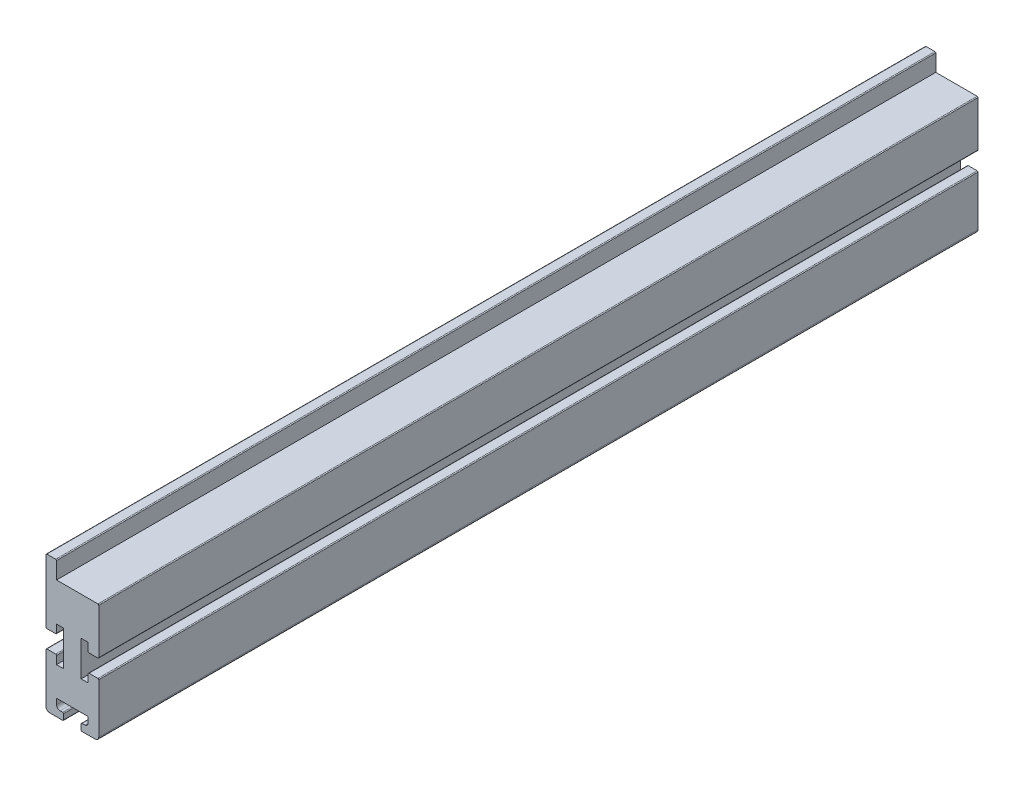
SolidWorks part; units mm, degrees
ref_plane "Alzado" through (0, 0, 0) normal (0, 0, 1) x (1, 0, 0)
ref_plane "Planta" through (0, 0, 0) normal (0, 1, 0) x (1, 0, 0)
ref_plane "Vista lateral" through (0, 0, 0) normal (1, 0, 0) x (0, 0, -1)
sketch "Croquis1" plane through (0, 0, 0) normal (0, 0, 1) x (1, 0, 0)
  line L1 (-4.4519, 8.3151) -> (1.5481, 8.3151)
  line L2 (1.5481, 8.3151) -> (1.5481, 13.3151)
  line L3 (1.5481, 13.3151) -> (5.5481, 13.3151)
  line L22 (1.5481, 35.0151) -> (1.5481, 45.0151)
  line L23 (1.5481, 45.0151) -> (-4.4519, 45.0151)
  line L24 (-4.4519, 45.0151) -> (-4.4519, 8.3151)
  line L31 (5.5481, 13.3151) -> (5.5481, -6.6849)
  line L35 (1.5481, 35.0151) -> (25.5481, 35.0151)
  line L38 (25.5481, 35.0151) -> (25.5481, 8.3151)
  line L39 (25.5481, 8.3151) -> (19.5481, 8.3151)
  line L40 (19.5481, 8.3151) -> (19.5481, 13.3151)
  line L42 (19.5481, 13.3151) -> (15.5481, 13.3151)
  line L44 (15.5481, 13.3151) -> (15.5481, -6.6849)
  line L47 (19.5481, -6.6849) -> (15.5481, -6.6849)
  line L48 (19.5481, -1.6849) -> (19.5481, -6.6849)
  line L49 (25.5481, -1.6849) -> (19.5481, -1.6849)
  line L55 (1.5481, -6.6849) -> (5.5481, -6.6849)
  line L56 (1.5481, -1.6849) -> (1.5481, -6.6849)
  line L57 (-4.4519, -1.6849) -> (1.5481, -1.6849)
  line L58 (-4.4519, -1.6849) -> (-4.4519, -32.3849)
  line L59 (-4.4519, -32.3849) -> (5.5481, -32.3849)
  line L60 (5.5481, -32.3849) -> (5.5481, -28.3849)
  line L61 (5.5481, -28.3849) -> (1.5481, -28.3849)
  line L62 (1.5481, -28.3849) -> (1.5481, -23.2502)
  line L63 (1.5481, -23.2502) -> (19.5481, -23.2502)
  line L64 (19.5481, -23.2502) -> (19.5481, -28.3849)
  line L65 (19.5481, -28.3849) -> (15.5481, -28.3849)
  line L66 (15.5481, -28.3849) -> (15.5481, -32.3849)
  line L67 (15.5481, -32.3849) -> (25.5481, -32.3849)
  line L68 (25.5481, -32.3849) -> (25.5481, -1.6849)
  point P13 (15.5481, 3.3151)
  point P20 (5.5481, 3.3151)
extrude "Saliente-Extruir1" add sketch "Croquis1" along normal blind 500
fillet "Redondeo1" radius 2 2 edges at (-4.4519, -32.3849, 250) (25.5481, -32.3849, 250)
fillet "Redondeo2" radius 2 2 edges at (19.5481, -28.3849, 250) (1.5481, -28.3849, 250)
fillet "Redondeo4" radius 0.5 15 edges at (-4.4519, 8.3151, 250) (19.5481, -1.6849, 250) (-4.4519, -1.6849, 250) (1.5481, -1.6849, 250) (25.5481, -1.6849, 250) (25.5481, 8.3151, 250) (19.5481, 8.3151, 250) (1.5481, 8.3151, 250) (15.5481, -32.3849, 250) (15.5481, -28.3849, 250) (5.5481, -32.3849, 250) (5.5481, -28.3849, 250) (25.5481, 35.0151, 250) (1.5481, 45.0151, 250) (-4.4519, 45.0151, 250)
